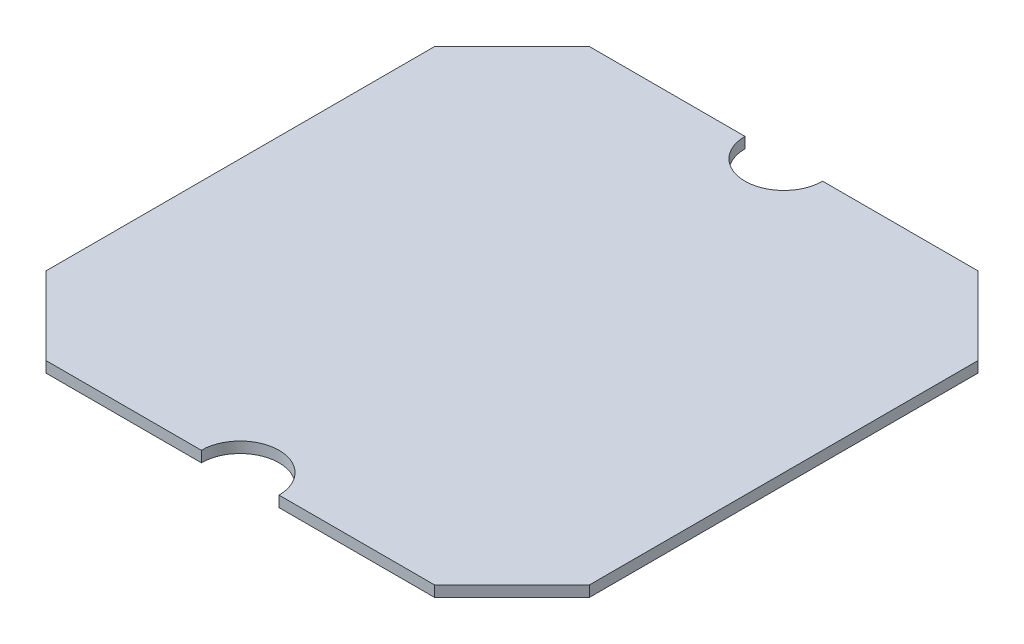
SolidWorks part; units mm, degrees
ref_plane "Front Plane" through (0, 0, 0) normal (0, 0, 1) x (1, 0, 0)
ref_plane "Top Plane" through (0, 0, 0) normal (0, 1, 0) x (1, 0, 0)
ref_plane "Right Plane" through (0, 0, 0) normal (1, 0, 0) x (0, 0, -1)
sketch "Sketch1" plane through (0, 0, 0) normal (0, 1, 0) x (1, 0, 0)
  line L0 (0, 175) -> (0, -175) construction
  line L1 (-125, 175) -> (-25, 175)
  line L2 (-175, 125) -> (-175, -125)
  line L3 (-125, -175) -> (-25, -175)
  line L4 (175, 125) -> (175, -125)
  line L7 (-175, 0) -> (175, 0) construction
  line L8 (-175, 125) -> (-125, 175)
  line L9 (125, 175) -> (175, 125)
  line L10 (175, -125) -> (125, -175)
  line L11 (-125, -175) -> (-175, -125)
  line L14 (25, -175) -> (125, -175)
  line L15 (25, 175) -> (125, 175)
  arc A0 (-25, 175) -> (25, 175) centre (0, 175) ccw
  arc A1 (25, -175) -> (-25, -175) centre (0, -175) ccw
  point P0 (0, 0)
  point P1 (-432.7123, 120.324)
  dimension "D3" = 50
  dimension "D4" = 50
  dimension "D7" = 4
extrude "Boss-Extrude1" add sketch "Sketch1" along normal blind 7
